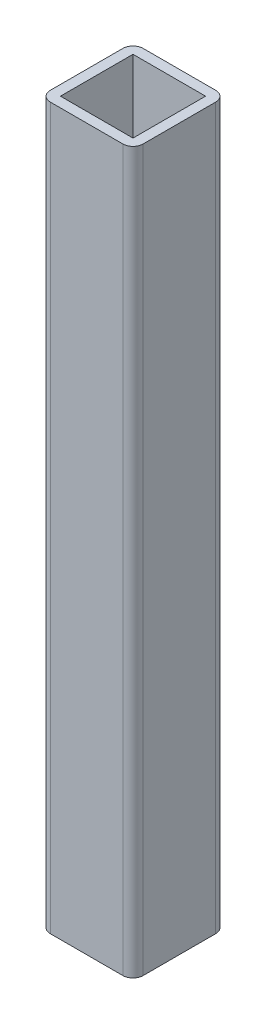
SolidWorks part; units mm, degrees
ref_plane "Front Plane" through (0, 0, 0) normal (0, 0, 1) x (1, 0, 0)
ref_plane "Top Plane" through (0, 0, 0) normal (0, 1, 0) x (1, 0, 0)
ref_plane "Right Plane" through (0, 0, 0) normal (1, 0, 0) x (0, 0, -1)
sketch "Sketch1" plane through (0, 0, 0) normal (0, 1, 0) x (1, 0, 0)
  line L1 (2.8, 0) -> (22.8, 0)
  line L2 (0, -2.8) -> (0, -22.8)
  line L3 (2.8, -25.6) -> (22.8, -25.6)
  line L4 (25.6, -2.8) -> (25.6, -22.8)
  arc A0 (22.8, 0) -> (25.6, -2.8) centre (22.8, -2.8) cw
  arc A1 (22.8, -25.6) -> (25.6, -22.8) centre (22.8, -22.8) ccw
  arc A2 (0, -22.8) -> (2.8, -25.6) centre (2.8, -22.8) ccw
  arc A3 (2.8, 0) -> (0, -2.8) centre (2.8, -2.8) ccw
  point P7 (25.6, 0)
  point P10 (25.6, -25.6)
  point P15 (0, 0)
  dimension "D2" = 2.8
  dimension "D1" = 25.6
extrude "Boss-Extrude1" add sketch "Sketch1" along normal blind 198.5
sketch "Sketch3" plane through (0, 0, 0) normal (0, -1, 0) x (-1, 0, 0)
  line L4 (-2.8, -2.8) -> (-22.8, -2.8)
  line L5 (-2.8, -2.8) -> (-2.8, -22.8)
  line L6 (-2.8, -22.8) -> (-22.8, -22.8)
  line L7 (-22.8, -2.8) -> (-22.8, -22.8)
  line L8 (-2.8, -2.8) -> (-22.8, -22.8) construction
  line L9 (-2.8, -22.8) -> (-22.8, -2.8) construction
  point P6 (-12.8, -12.8)
extrude "Cut-Extrude1" cut sketch "Sketch3" against normal blind 861
